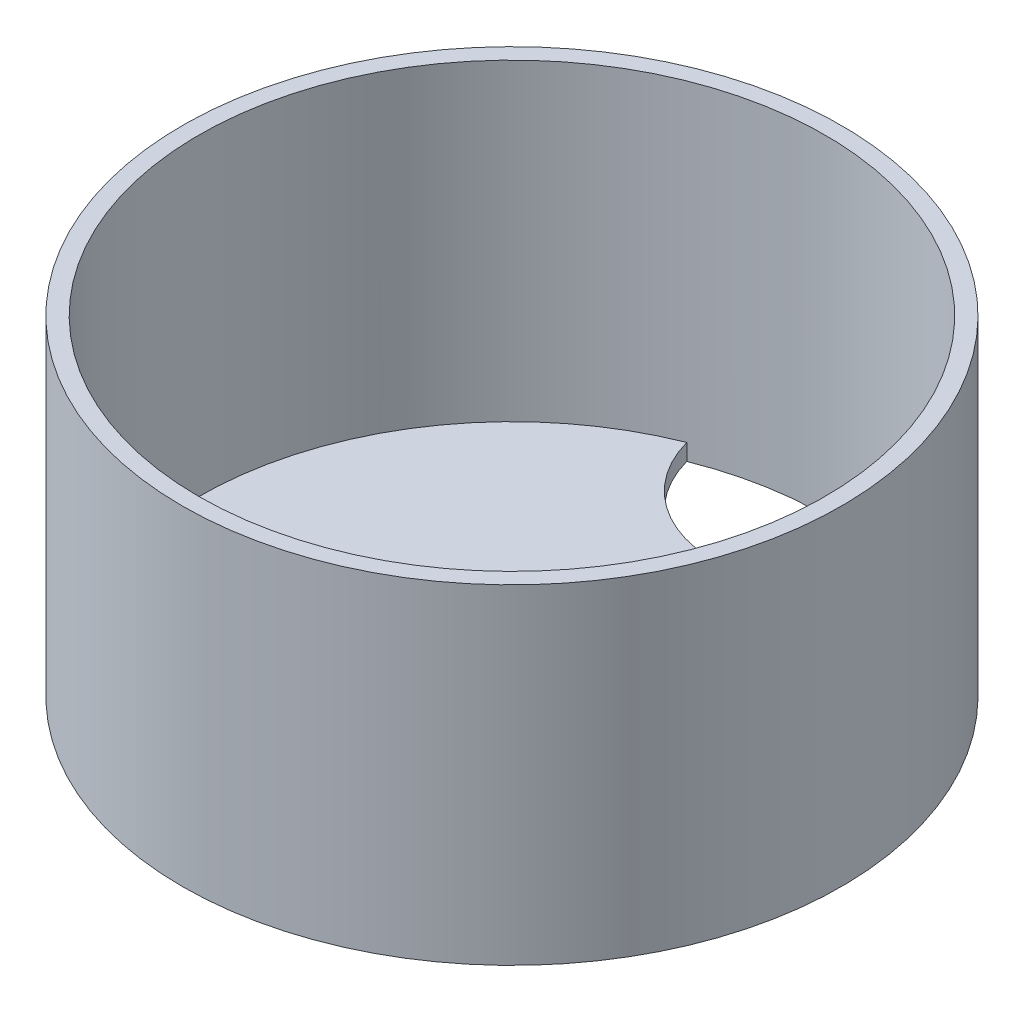
SolidWorks part; units mm, degrees
ref_plane "Front Plane" through (0, 0, 0) normal (0, 0, 1) x (1, 0, 0)
ref_plane "Top Plane" through (0, 0, 0) normal (0, 1, 0) x (1, 0, 0)
ref_plane "Right Plane" through (0, 0, 0) normal (1, 0, 0) x (0, 0, -1)
sketch "Sketch1" plane through (0, 0, 0) normal (0, 1, 0) x (1, 0, 0)
  circle A0 centre (0, 0) radius 40
extrude "Boss-Extrude1" add sketch "Sketch1" along normal blind 40 contours A0
sketch "Sketch2" plane through (0, 40, 0) normal (0, 1, 0) x (1, 0, 0)
  circle A0 centre (0, 0) radius 38
extrude "Cut-Extrude1" cut sketch "Sketch2" against normal blind 38
sketch "Sketch3" plane through (0, 2, 0) normal (0, 1, 0) x (1, 0, 0)
  arc A0 (-14.0761, 35.2968) -> (14.0761, 35.2968) centre (0, 39.1212) ccw
  circle A1 centre (0, 0) radius 38 construction
  circle A2 centre (0, 0) radius 38 construction
  arc A3 (-14.0761, 35.2968) -> (14.0761, 35.2968) centre (0, 0) cw
extrude "Cut-Extrude2" cut sketch "Sketch3" against normal blind 38
sketch "Sketch4" plane through (0, 2, 0) normal (0, 1, 0) x (1, 0, 0)
  circle A0 centre (0, 0) radius 5
extrude "Cut-Extrude3" cut sketch "Sketch4" against normal blind 38
